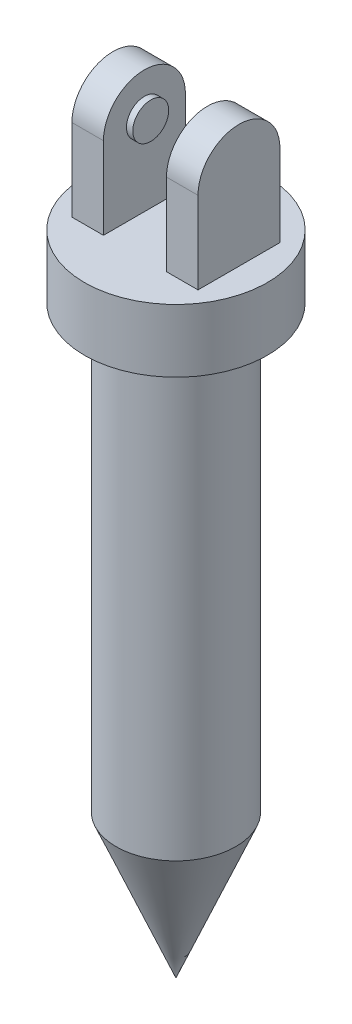
SolidWorks part; units mm, degrees
ref_plane "Front Plane" through (0, 0, 0) normal (0, 0, 1) x (1, 0, 0)
ref_plane "Top Plane" through (0, 0, 0) normal (0, 1, 0) x (1, 0, 0)
ref_plane "Right Plane" through (0, 0, 0) normal (1, 0, 0) x (0, 0, -1)
sketch "Sketch1" plane through (0, 0, 0) normal (0, 1, 0) x (1, 0, 0)
  circle A0 centre (0, 0) radius 14.5
  dimension "D1" = 29
extrude "Boss-Extrude1" add sketch "Sketch1" along normal blind 10
sketch "Sketch2" plane through (0, 10, 0) normal (0, 1, 0) x (1, 0, 0)
  line L0 (-10, 0) -> (-10, 10)
  line L1 (-10, 10) -> (10, 10)
  line L2 (10, 10) -> (10, -10)
  line L3 (10, -10) -> (-10, -10)
  line L4 (-10, -10) -> (-10, 0)
extrude "Boss-Extrude2" add sketch "Sketch2" along normal blind 20
sketch "Sketch3" plane through (-10, 0, 0) normal (-1, 0, 0) x (0, 0, 1)
  line L0 (0, 10) -> (0, 23) construction
  line L1 (14.5, 10) -> (-14.5, 10) construction
  line L2 (0, -55) -> (0, 55) construction
  line L3 (-6.5, 23) -> (-6.5, 10)
  line L4 (-10, 10) -> (10, 10) construction
  line L5 (6.5, 23) -> (6.5, 10)
  line L6 (6.5, 10) -> (10, 10)
  line L7 (10, 10) -> (10, 30)
  line L8 (-10, 30) -> (10, 30)
  line L10 (-10, 30) -> (-10, 10)
  line L11 (-10, 10) -> (-6.5, 10)
  arc A1 (6.5, 23) -> (-6.5, 23) centre (0, 23) ccw
  dimension "D1" = 13
  dimension "D3" = 6.5
extrude "Cut-Extrude1" cut sketch "Sketch3" against normal blind 20
sketch "Sketch5" plane through (0, 0, 6.5) normal (0, 0, 1) x (1, 0, 0)
  line L0 (14.5, 10) -> (-14.5, 10) construction
  line L1 (-5, 10) -> (5, 10)
  line L2 (-5, 10) -> (-5, 30)
  line L3 (-5, 30) -> (5, 30)
  line L4 (5, 10) -> (5, 30)
  line L6 (-10, 23) -> (-10, 10) construction
  line L7 (10, 23) -> (10, 10) construction
  dimension "D1" = 5
  dimension "D2" = 5
  dimension "D3" = 20
extrude "Cut-Extrude2" cut sketch "Sketch5" against normal blind 20
sketch "Sketch6" plane through (-5, 0, 0) normal (1, 0, 0) x (0, 0, -1)
  circle A0 centre (0, 23) radius 2.85
  dimension "D1" = 5.7
extrude "Boss-Extrude3" add sketch "Sketch6" along normal blind 1
mirror "Mirror1" about plane through (0, 0, 0) normal (1, 0, 0) of "Boss-Extrude3"
scale "Scale1" scale about origin uniform scaling yes scale factor 0.5
sketch "Sketch7" plane through (0, 0, 0) normal (0, -1, 0) x (1, 0, 0)
  circle A0 centre (0, 0) radius 4.75
  dimension "D1" = 9.5
extrude "Boss-Extrude4" add sketch "Sketch7" along normal blind 35
sketch "Sketch8" plane through (0, 0, 0) normal (0, 0, 1) x (1, 0, 0)
  line L0 (0, -35) -> (4.75, -35)
  line L1 (-4.75, -35) -> (4.75, -35) construction
  line L2 (0, -35) -> (0, -46.4)
  line L3 (0, -15.95) -> (0, 15.95) construction
  line L4 (0, -46.4) -> (4.75, -35)
  dimension "D1" = 67.38
revolve "Revolve1" add sketch "Sketch8" angle 360 about L2
